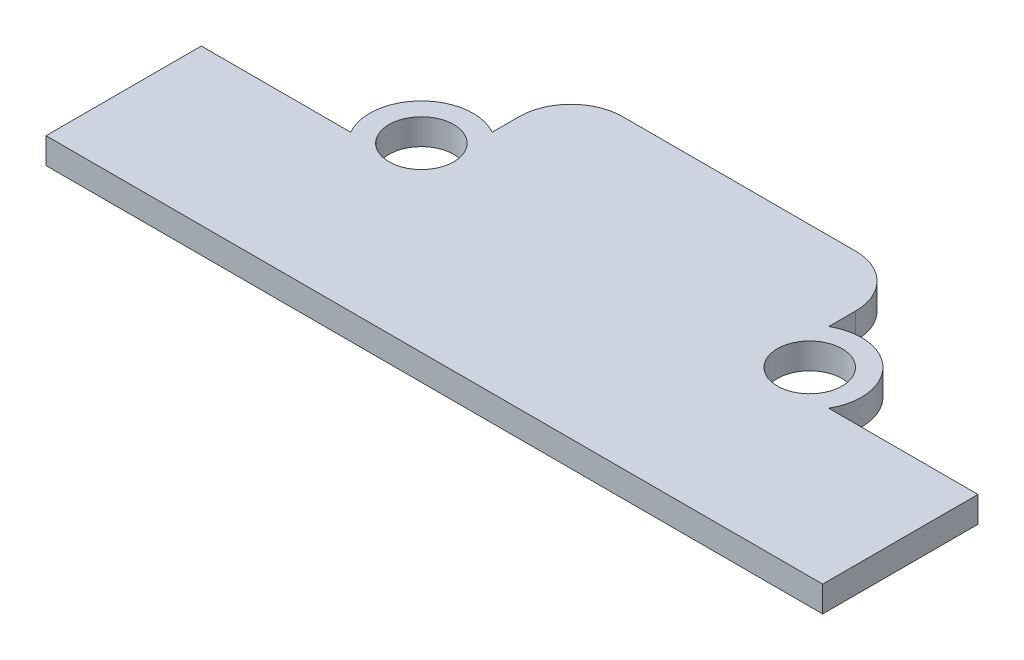
SolidWorks part; units mm, degrees
ref_plane "Plan de face" through (0, 0, 0) normal (0, 0, 1) x (1, 0, 0)
ref_plane "Plan de dessus" through (0, 0, 0) normal (0, 1, 0) x (1, 0, 0)
ref_plane "Plan de droite" through (0, 0, 0) normal (1, 0, 0) x (0, 0, -1)
sketch "Esquisse1" plane through (0, 0, 0) normal (0, 1, 0) x (1, 0, 0)
  line L0 (21.5, 6) -> (30, 6)
  line L1 (0, 0) -> (30, 0)
  line L2 (0, 0) -> (0, 6)
  line L3 (0, 6) -> (8.5, 6)
  line L4 (30, 0) -> (30, 6)
  line L6 (8.5, 6) -> (8.5, 11.775)
  line L7 (8.5, 11.775) -> (21.5, 11.775)
  line L8 (21.5, 6) -> (21.5, 11.775)
  dimension "D1" = 6
  dimension "D2" = 30
  dimension "D4" = 13
extrude "Boss.-Extru.1" add sketch "Esquisse1" along normal blind 1
sketch "Esquisse2" plane through (0, 1, 0) normal (0, 1, 0) x (1, 0, 0)
  line L0 (8.5, 11.775) -> (8.5, 6) construction
  line L2 (8.5, 6) -> (0, 6) construction
  line L3 (21.5, 6) -> (21.5, 11.775) construction
  line L4 (30, 6) -> (21.5, 6) construction
  circle A0 centre (7.5, 7) radius 2
  circle A1 centre (22.5, 7) radius 2
  point P6 (0, 0)
  point P8 (7.1949, 6)
  point P10 (4.25, 6)
  point P13 (21.5, 8.8875)
  dimension "D1" = 4
  dimension "D2" = 4
  dimension "D3" = 1
  dimension "D4" = 1
  dimension "D5" = 1
  dimension "D6" = 1
extrude "Boss.-Extru.2" add sketch "Esquisse2" against normal blind 1
sketch "Esquisse3" plane through (0, 1, 0) normal (0, 1, 0) x (1, 0, 0)
  circle A0 centre (7.5, 7) radius 1.25
  circle A1 centre (22.5, 7) radius 1.25
  dimension "D1" = 2.5
  dimension "D2" = 2.5
extrude "Enlèv. mat.-Extru.1" cut sketch "Esquisse3" against normal through all
fillet "Congé1" radius 2 2 edges at (21.5, 0.5, -11.775) (8.5, 0.5, -11.775)
